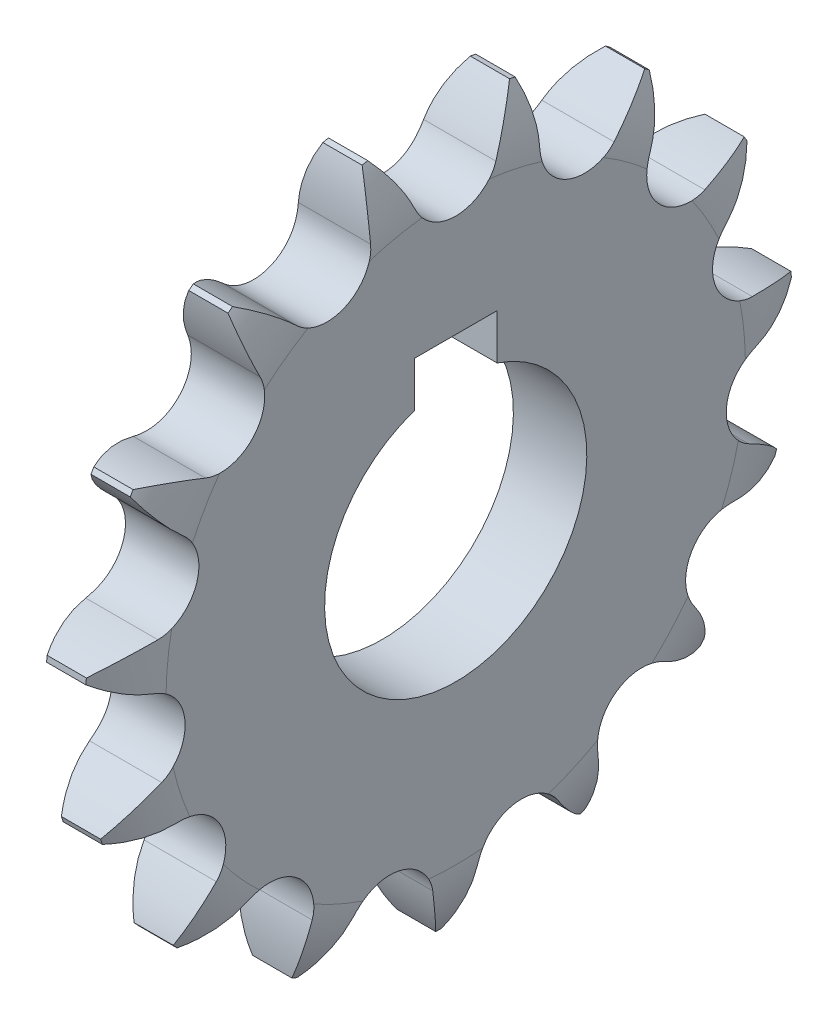
SolidWorks part; units mm, degrees
ref_plane "Plane1" through (0, 0, 0) normal (0, 0, 1) x (1, 0, 0)
ref_plane "Plane2" through (0, 0, 0) normal (0, 1, 0) x (1, 0, 0)
ref_plane "Plane3" through (0, 0, 0) normal (1, 0, 0) x (0, 0, -1)
sketch "Clipboard" plane through (0, 0, 0) normal (0, 1, 0) x (1, 0, 0)
  line L0 (0, 0) -> (9.2004, -2.4653)
  line L1 (-15, 0) -> (100, 0) construction
  line L2 (0, 0) -> (-0.8203, 0.9272)
  line L3 (0, 0) -> (-8.8973, 3.4006)
  line L4 (0, 0) -> (2.9944, 0.8023)
  line L5 (0, 0) -> (-46.8476, -17.4728)
  line L6 (0, 0) -> (-4.4098, -2.9753)
  line L7 (-0.8203, 0.9272) -> (47.2432, 14.7092)
  line L8 (-76.2, 38.1) -> (-73.4, 38.1)
  line L9 (-73.3242, 40.7328) -> (-72.926, 40.7699)
  line L10 (-73.4529, 9.1872) -> (-63.2129, 9.1872)
  circle A0 centre (0, 0) radius 3.175
  circle A1 centre (0, 0) radius 17.7306
  circle A2 centre (0, 0) radius 37.5
  dimension "Dr" = 6.35
  dimension "MHD" = 35.4612
  dimension "Hub_dia" = 75
  dimension "Num_teeth" = 15
  dimension "Pitch" = 9.525
  dimension "Width" = 3.1
  dimension "Side_relief" = 1.238
  dimension "Side_radius" = 9.525
  dimension "Overall_len" = 50
  dimension "Show_teeth" = 15
  dimension "Thickness" = 5.3196
  dimension "OAL" = 50.0005
  dimension "T_dim" = 2.8
  dimension "Fillet_rad" = 0.4
  dimension "Face_width" = 5.32
  dimension "Num_strands" = 1
  dimension "Transv_pitch" = 10.24
  dimension "Plate_wid" = 8.26
sketch "BasProSke" plane through (0, 0, 0) normal (0, 1, 0) x (1, 0, 0)
  line L0 (-10, 0) -> (60, 0) construction
  line L1 (0, 0) -> (0, 20.9886)
  line L2 (0, 0) -> (5.3196, 0)
  line L3 (5.3196, 0) -> (5.3196, 20.9886)
  line L4 (4.0816, 25.6845) -> (1.238, 25.6845)
  arc A0 (0, 20.9886) -> (1.238, 25.6845) centre (9.525, 20.9886) cw
  arc A1 (5.3196, 20.9886) -> (4.0816, 25.6845) centre (-4.2054, 20.9886) ccw
  dimension "Thickness" = 5.3196
  dimension "D1" = 9.525
  dimension "G1" = 1.238
  dimension "G2" = 1.238
  dimension "Diameter" = 51.369
revolve "Base-Revolve" add sketch "BasProSke" angle 360 about L0
sketch "TooCutSke" plane through (0, 0, 0) normal (1, 0, 0) x (0, 0, -1)
  line L0 (0, 22.9381) -> (2.9518, 21.6851) construction
  line L1 (0, 0) -> (0, 107) construction
  line L2 (0, 22.9381) -> (-10, 22.9381) construction
  line L3 (0, 22.9381) -> (-2.9518, 21.6851) construction
  arc A0 (2.9518, 21.6851) -> (5.5304, 25.5938) centre (14.876, 16.6236) cw
  arc A1 (2.9518, 21.6851) -> (-2.9518, 21.6851) centre (0, 22.9381) cw
  arc A2 (-2.9518, 21.6851) -> (-5.5304, 25.5938) centre (-14.876, 16.6236) ccw
  arc A3 (5.5304, 25.5938) -> (-5.5304, 25.5938) centre (0, 0) ccw
  dimension "R1" = 3.2067
  dimension "R2" = 12.954
  dimension "Overcut" = 26.1845
  dimension "Seat_radius" = 22.9381
  dimension "X" = 134
extrude "ToothCut" cut sketch "TooCutSke" along normal through all
pattern_circular "TeethCuts" count 15 every 24 about axis through (-10, 0, 0) along (1, 0, 0) of "ToothCut"
sketch "HubNeaOneSke" plane through (0, 0, 0) normal (-1, 0, 0) x (0, 0, 1)
  circle A0 centre (0, 0) radius 17.7306
  dimension "Diameter" = 35.4612
extrude "HubNearOne" [suppressed] add sketch "HubNeaOneSke" along normal blind 44.6809
fillet "HubNearOneFillet" [suppressed] radius 0.4
sketch "HubNeaBotSke" plane through (0, 0, 0) normal (-1, 0, 0) x (0, 0, 1)
  circle A0 centre (0, 0) radius 17.7306
  dimension "Diameter" = 35.4612
extrude "HubNearBoth" [suppressed] add sketch "HubNeaBotSke" along normal blind 22.3405
fillet "HubNearBothFillet" [suppressed] radius 0.4
ref_plane "FarPln" through (5.3196, 0, 0) normal (1, 0, 0) x (0, 0, -1)
sketch "HubFarSke" plane through (5.3196, 0, 0) normal (1, 0, 0) x (0, 0, -1)
  circle A0 centre (0, 0) radius 17.7306
  dimension "Diameter" = 35.4612
extrude "HubFar" [suppressed] add sketch "HubFarSke" along normal blind 22.3405
fillet "HubFarFillet" [suppressed] radius 0.4
sketch "BorSke" plane through (0, 0, 0) normal (1, 0, 0) x (0, 0, -1)
  circle A0 centre (0, 0) radius 9.5
  dimension "Diameter" = 19
extrude "Bore" cut sketch "BorSke" along normal mid plane 100.001
sketch "KeySke" plane through (0, 0, 0) normal (1, 0, 0) x (0, 0, -1)
  line L0 (-3, 0) -> (-3, 12.3)
  line L1 (-3, 12.3) -> (3, 12.3)
  line L2 (3, 12.3) -> (3, 0)
  line L3 (0, 0) -> (0, 34) construction
  line L4 (-3, 0) -> (3, 0)
  dimension "Offset" = 12.3
  dimension "Width" = 6
extrude "Keyway" cut sketch "KeySke" along normal mid plane 100.001
pattern_circular "Keyway2" [suppressed] count 2 every 90 about axis through (-10, 0, 0) along (1, 0, 0)
equation "' \"Pitch@Clipboard\" = 12.7"
equation "' \"Num_strands@Clipboard\" = 1"
equation "' \"Num_teeth@Clipboard\" = 9"
equation "' \"Hub_dia@Clipboard\" = 50"
equation "' \"Overall_len@Clipboard\" = 3"
equation "' \"Diameter@BorSke\" = 12"
equation "' \"T_dim@Clipboard\" = 1"
equation "' \"Width@KeySke\" = 2"
equation "' \"Dr@Clipboard\" = 8.51"
equation "' \"Face_width@Clipboard\" = 7.2"
equation "' \"Side_radius@Clipboard\" = 12.7"
equation "' \"Side_relief@Clipboard\" = 1.27"
equation "' \"Transv_pitch@Clipboard\" = 13.92"
equation "' \"Show_teeth@Clipboard\" = 9"
equation "' \"Fillet_rad@Clipboard\" = 0.6"
equation "' \"Plate_wid@Clipboard\" = 11.8"
equation "\"Num_teeth@Clipboard\" = int( \"Num_teeth@Clipboard\" )"
equation "\"Num_teeth@Clipboard\" = ((sgn( \"Num_teeth@Clipboard\" - 5.0)+1)*( \"Num_teeth@Clipboard\" - 5.0))/2 +5.0"
equation "\"Num_teeth@Clipboard\" = ((sgn( \"Num_teeth@Clipboard\" - 200.0)-1)*( \"Num_teeth@Clipboard\" - 200.0))/-2 +200.0"
equation "\"MHD@Clipboard\" = \"Pitch@Clipboard\" * (1.0 / tan(3.14159265 / \"Num_teeth@Clipboard\" )) - 1.04 * \"Plate_wid@Clipboard\" - 0.76"
equation "\"Thickness@Clipboard\"  = \"Face_width@Clipboard\" + (\"Num_strands@Clipboard\" - 1) * \"Transv_pitch@Clipboard\""
equation "\"OAL@Clipboard\" = \"Thickness@Clipboard\" + 2 * \"Fillet_rad@Clipboard\" + 1"
equation "\"MHD@Clipboard\" = ((sgn( \"MHD@Clipboard\" - \"Hub_dia@Clipboard\" )-1)*( \"MHD@Clipboard\" - \"Hub_dia@Clipboard\" ))/-2+ \"Hub_dia@Clipboard\""
equation "\"OAL@Clipboard\" = ((sgn( \"OAL@Clipboard\" - \"Overall_len@Clipboard\" )+1)*( \"OAL@Clipboard\" - \"Overall_len@Clipboard\" ))/2 + \"Overall_len@Clipboard\" + 0.0005"
equation "\"Num_teeth@TeethCuts\" = int( \"Show_teeth@Clipboard\" ) + 1"
equation "\"Num_teeth@TeethCuts\" = ((sgn( \"Num_teeth@TeethCuts\" - \"Num_teeth@Clipboard\" )-1)*( \"Num_teeth@TeethCuts\" - \"Num_teeth@Clipboard\" ))/-2+ \"Num_teeth@Clipboard\""
equation "\"Num_teeth@TeethCuts\" = ((sgn( \"Num_teeth@TeethCuts\" - 2.0)+1)*( \"Num_teeth@TeethCuts\" - 2.0))/2 +2.0"
equation "\"Angle@TeethCuts\" = 360.0 / \"Num_teeth@Clipboard\""
equation "\"Seat_radius@TooCutSke\" = ( \"Pitch@Clipboard\" / 2.0) / sin(3.14159265 / \"Num_teeth@Clipboard\" ) - \"Dr@Clipboard\" / 2.0 + \"Dr@Clipboard\" * 0.505"
equation "\"R1@TooCutSke\"  = \"Dr@Clipboard\" * 0.505"
equation "\"X@TooCutSke\" = 140.0 - (90.0 / \"Num_teeth@Clipboard\")"
equation "\"R2@TooCutSke\" = 0.12 * \"Dr@Clipboard\" * ( \"Num_teeth@Clipboard\" + 2.0)"
equation "\"Overcut@TooCutSke\" = 0.5 + 0.625 * \"Pitch@Clipboard\" - 0.5 * \"Dr@Clipboard\"  +  \"Pitch@Clipboard\" / 2.0 / sin(3.14159265 / \"Num_teeth@Clipboard\" )"
equation "\"Diameter@BasProSke\" = 2.0 * ( 0.625 * \"Pitch@Clipboard\" - 0.5 * \"Dr@Clipboard\"  +  \"Pitch@Clipboard\" / 2.0 / sin(3.14159265 / \"Num_teeth@Clipboard\" ))"
equation "\"Thickness@BasProSke\"  = \"Thickness@Clipboard\""
equation "\"G1@BasProSke\" =  \"Side_relief@Clipboard\""
equation "\"G2@BasProSke\" =  \"Side_relief@Clipboard\""
equation "\"D1@BasProSke\" =  \"Side_radius@Clipboard\""
equation "\"Diameter@HubNeaOneSke\" = \"MHD@Clipboard\""
equation "\"Length@HubNearOne\" = \"OAL@Clipboard\" - \"Thickness@BasProSke\""
equation "\"Diameter@HubNeaBotSke\" = \"MHD@Clipboard\""
equation "\"Length@HubNearBoth\" = ( \"OAL@Clipboard\" - \"Thickness@BasProSke\" ) / 2.0"
equation "\"D1@HubNearOneFillet\" = \"Fillet_rad@Clipboard\""
equation "\"D1@HubNearBothFillet\" = \"Fillet_rad@Clipboard\""
equation "\"Thickness@FarPln\" = \"Thickness@BasProSke\""
equation "\"Diameter@HubFarSke\" = \"MHD@Clipboard\""
equation "\"Length@HubFar\" = ( \"OAL@Clipboard\" - \"Thickness@BasProSke\" ) / 2.0"
equation "\"D1@HubFarFillet\" = \"Fillet_rad@Clipboard\""
equation "\"D1@Bore\" = \"OAL@Clipboard\" * 2.0"
equation "\"D1@Keyway\" = \"OAL@Clipboard\" * 2.0"
equation "\"Offset@KeySke\" = \"T_dim@Clipboard\" + \"Diameter@BorSke\" / 2.0"
